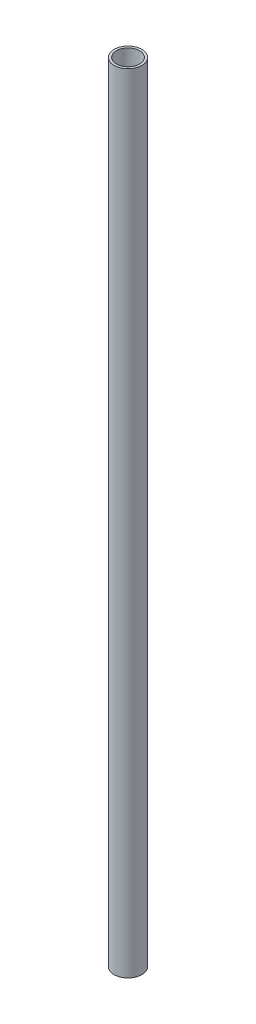
SolidWorks part; units mm, degrees
material "Thornel Mat VMA"
ref_plane "前视基准面" through (0, 0, 0) normal (0, 0, 1) x (1, 0, 0)
ref_plane "上视基准面" through (0, 0, 0) normal (0, 1, 0) x (1, 0, 0)
ref_plane "右视基准面" through (0, 0, 0) normal (1, 0, 0) x (0, 0, -1)
sketch "草图1" plane through (0, 0, 0) normal (0, 1, 0) x (1, 0, 0)
  circle A0 centre (0, 0) radius 5
  circle A1 centre (0, 0) radius 6
  dimension "D1" = 12
  dimension "D2" = 1
extrude "凸台-拉伸1" add sketch "草图1" along normal blind 340
